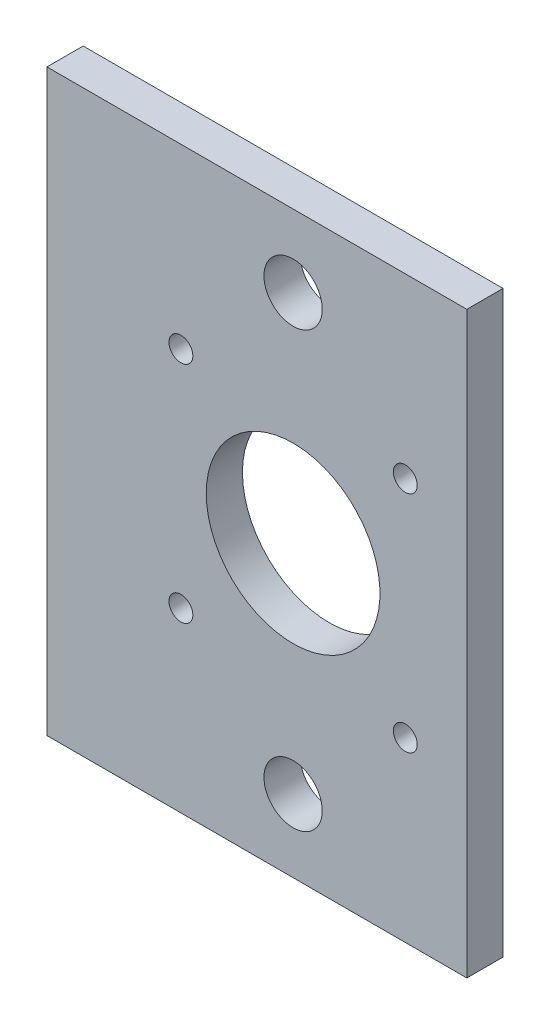
SolidWorks part; units mm, degrees
ref_plane "Plan de face" through (0, 0, 0) normal (0, 0, 1) x (1, 0, 0)
ref_plane "Plan de dessus" through (0, 0, 0) normal (0, 1, 0) x (1, 0, 0)
ref_plane "Plan de droite" through (0, 0, 0) normal (1, 0, 0) x (0, 0, -1)
sketch "Sketch1" plane through (0, 0, 0) normal (0, 0, 1) x (1, 0, 0)
  line L1 (32.75, -40) -> (-32.75, -40)
  line L2 (32.75, -40) -> (32.75, 40)
  line L3 (32.75, 40) -> (-32.75, 40)
  line L4 (-32.75, -40) -> (-32.75, 40)
  line L5 (32.75, -40) -> (-32.75, 40) construction
  line L6 (32.75, 40) -> (-32.75, -40) construction
  point P0 (0, 0)
  dimension "D1" = 65.5
  dimension "D2" = 80
extrude "Boss-Extrude1" add sketch "Sketch1" along normal blind 5
sketch "Sketch2" plane through (0, 0, 5) normal (0, 0, 1) x (1, 0, 0)
  line L0 (32.75, 40) -> (-32.75, 40) construction
  line L1 (32.75, -40) -> (25.25, -40)
  line L2 (32.75, -40) -> (32.75, 40)
  line L3 (32.75, 40) -> (25.25, 40)
  line L4 (25.25, -40) -> (25.25, 40)
  line L5 (22.25, -16.5858) -> (22.25, 16.5858) construction
  dimension "D1" = 3
extrude "Cut-Extrude1" cut sketch "Sketch2" against normal through all
sketch "Sketch3" plane through (0, 0, 0) normal (0, 0, -1) x (-1, 0, 0)
  circle A0 centre (-1.25, 0) radius 12
  circle A1 centre (-16.75, 15.5) radius 1.65
  circle A2 centre (14.25, 15.5) radius 1.65
  circle A3 centre (14.25, -15.5) radius 1.65
  circle A4 centre (-16.75, -15.5) radius 1.65
  dimension "D1" = 3.3
  dimension "D2" = 3.3
  dimension "D3" = 3.3
  dimension "D4" = 3.3
  dimension "D5" = 24
extrude "Cut-Extrude2" cut sketch "Sketch3" against normal through all
sketch "Sketch4" plane through (0, 0, 0) normal (0, 0, -1) x (-1, 0, 0)
  line L0 (2.75, 0) -> (-2.75, 0) construction
  circle A0 centre (-1.25, 30) radius 4.025
  circle A1 centre (-1.25, -30) radius 4.025
  dimension "D1" = 8.05
extrude "Cut-Extrude3" cut sketch "Sketch4" against normal through all and the other way through all
